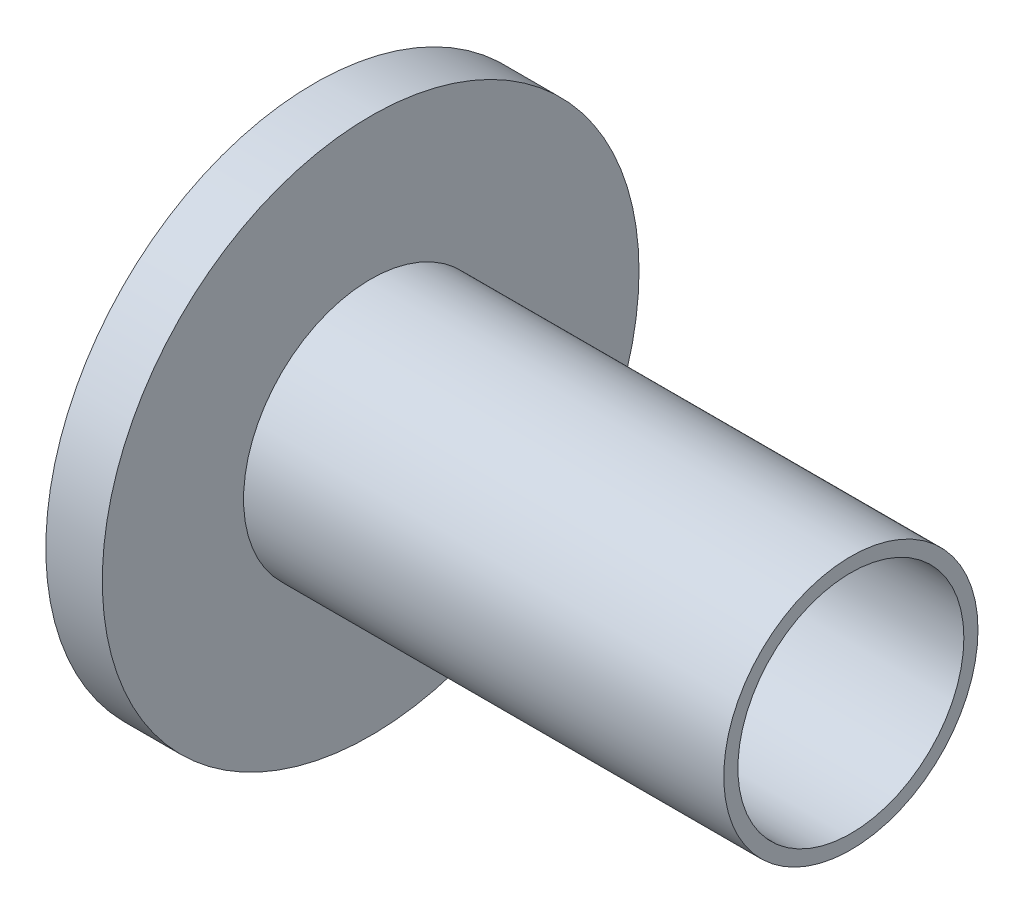
SolidWorks part; units mm, degrees
ref_plane "Front Plane" through (0, 0, 0) normal (0, 0, 1) x (1, 0, 0)
ref_plane "Top Plane" through (0, 0, 0) normal (0, 1, 0) x (1, 0, 0)
ref_plane "Right Plane" through (0, 0, 0) normal (1, 0, 0) x (0, 0, -1)
sketch "Sketch3" plane through (0, 0, 0) normal (0, 0, 1) x (1, 0, 0)
  line L0 (6, 8) -> (-11, 8)
  line L4 (-13, 8) -> (-11, 8)
  line L5 (6, 8) -> (6, 12.5)
  line L6 (6, 12.5) -> (-11, 12.5)
  line L7 (-13, 8) -> (-13, 17.5)
  line L8 (-13, 17.5) -> (-11, 17.5)
  line L9 (-11, 17.5) -> (-11, 12.5)
  dimension "D1" = 8
  dimension "D2" = 5
  dimension "D3" = 17
  dimension "D4" = 13
  dimension "D5" = 4.5
  dimension "D7" = 6
revolve "Revolve2" add sketch "Sketch3" angle 360 about L0
sketch "Sketch5" plane through (6, 0, 0) normal (1, 0, 0) x (0, 0, -1)
  circle A0 centre (0, 8) radius 4
  dimension "D1" = 8
extrude "Cut-Extrude2" cut sketch "Sketch5" against normal through all
